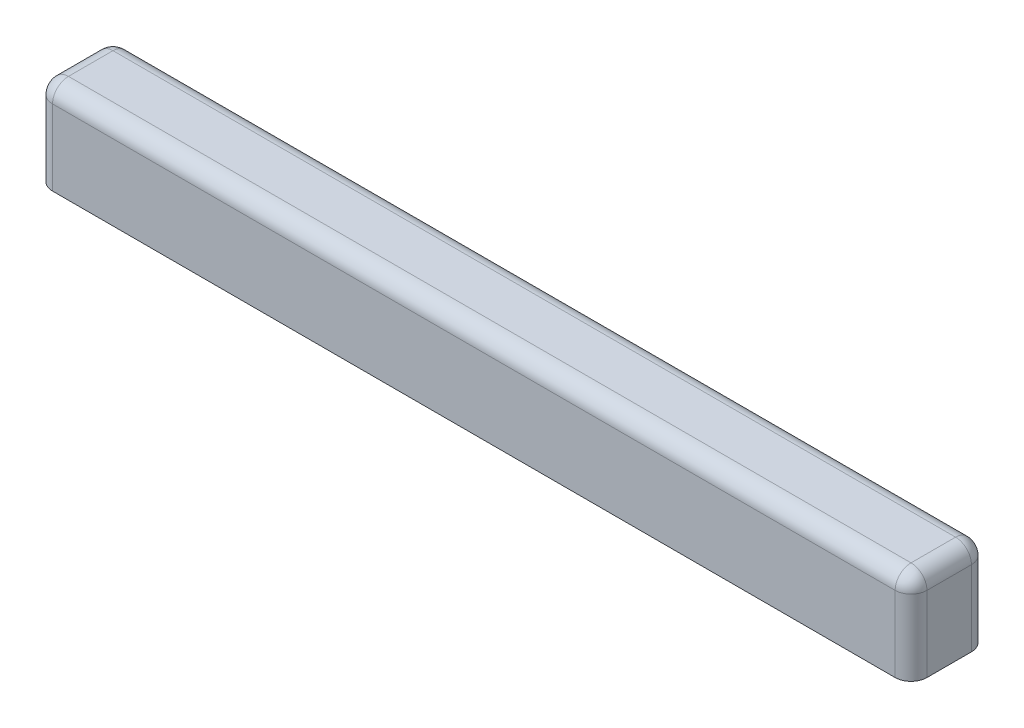
SolidWorks part; units mm, degrees
material "ABS"
ref_plane "Front Plane" through (0, 0, 0) normal (0, 0, 1) x (1, 0, 0)
ref_plane "Top Plane" through (0, 0, 0) normal (0, 1, 0) x (1, 0, 0)
ref_plane "Right Plane" through (0, 0, 0) normal (1, 0, 0) x (0, 0, -1)
sketch "Sketch1" plane through (0, 0, 0) normal (0, 1, 0) x (1, 0, 0)
  line L1 (-55, -4.8) -> (55, -4.8)
  line L2 (-55, -4.8) -> (-55, 4.8)
  line L3 (-55, 4.8) -> (55, 4.8)
  line L4 (55, -4.8) -> (55, 4.8)
  line L5 (-55, -4.8) -> (55, 4.8) construction
  line L6 (-55, 4.8) -> (55, -4.8) construction
  point P0 (0, 0)
  dimension "D1" = 110
  dimension "D2" = 9.6
extrude "Boss-Extrude1" add sketch "Sketch1" along normal blind 11.5
fillet "Fillet1" radius 2 8 edges at (0, 11.5, 4.8) (-55, 11.5, 0) (0, 11.5, -4.8) (55, 11.5, 0) (-55, 5.75, -4.8) (-55, 5.75, 4.8) (55, 5.75, -4.8) (55, 5.75, 4.8)
